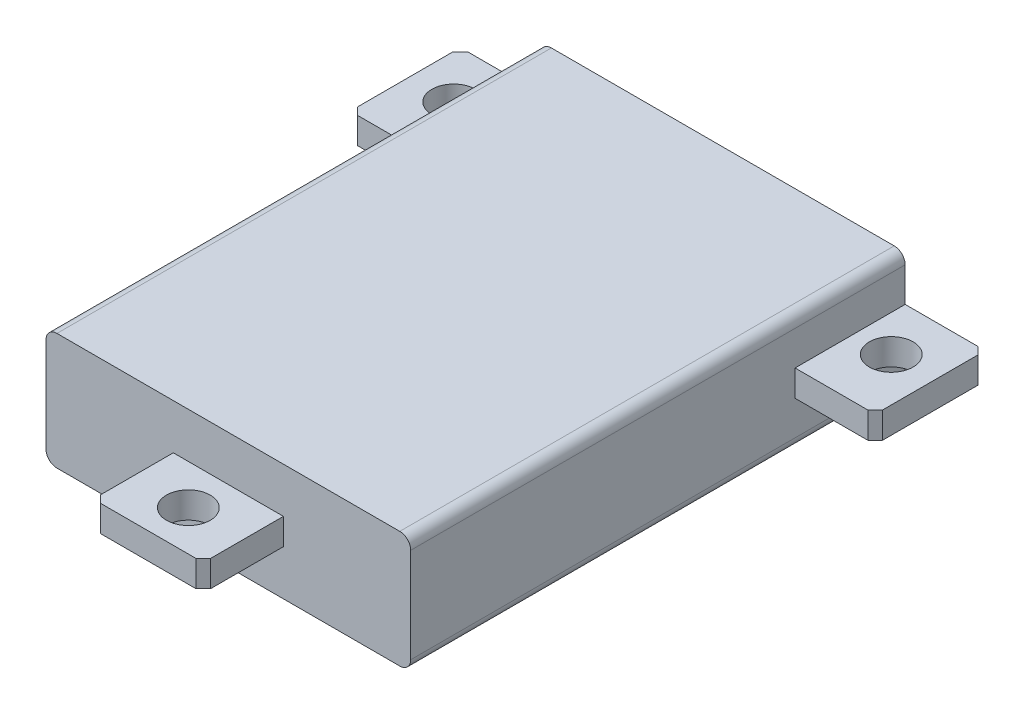
SolidWorks part; units mm, degrees
ref_plane "Front Plane" through (0, 0, 0) normal (0, 0, 1) x (1, 0, 0)
ref_plane "Top Plane" through (0, 0, 0) normal (0, 1, 0) x (1, 0, 0)
ref_plane "Right Plane" through (0, 0, 0) normal (1, 0, 0) x (0, 0, -1)
sketch "Sketch1" plane through (0, 0, 0) normal (0, 1, 0) x (1, 0, 0)
  line L1 (-12.505, -16.9525) -> (12.505, -16.9525)
  line L2 (-12.505, -16.9525) -> (-12.505, 16.9525)
  line L3 (-12.505, 16.9525) -> (12.505, 16.9525)
  line L4 (12.505, -16.9525) -> (12.505, 16.9525)
  line L5 (-12.505, -16.9525) -> (12.505, 16.9525) construction
  line L6 (-12.505, 16.9525) -> (12.505, -16.9525) construction
  point P0 (0, 0)
  dimension "D1" = 33.905
  dimension "D2" = 25.01
extrude "Boss-Extrude1" add sketch "Sketch1" along normal blind 8
sketch "Sketch2" plane through (0, 0, 16.9525) normal (0, 0, 1) x (1, 0, 0)
  line L0 (0, 0) -> (0, 4) construction
  line L2 (-3.775, 3.1) -> (3.775, 3.1)
  line L3 (-3.775, 3.1) -> (-3.775, 4.9)
  line L4 (-3.775, 4.9) -> (3.775, 4.9)
  line L5 (3.775, 3.1) -> (3.775, 4.9)
  line L6 (-3.775, 3.1) -> (3.775, 4.9) construction
  line L7 (-3.775, 4.9) -> (3.775, 3.1) construction
  dimension "D1" = 4
  dimension "D2" = 7.55
  dimension "D3" = 1.8
extrude "Boss-Extrude2" add sketch "Sketch2" along normal blind 5.495
sketch "Sketch3" plane through (-12.505, 0, 0) normal (-1, 0, 0) x (0, 0, 1)
  line L0 (-16.9525, 4) -> (-16.9525, 3.1) construction
  line L1 (-16.9525, 4) -> (-9.4025, 4) construction
  line L3 (-16.9525, 8) -> (-16.9525, 0) construction
  line L4 (-9.4025, 4) -> (-9.4025, 4.9) construction
  line L6 (-16.9525, 3.1) -> (-9.4025, 3.1)
  line L7 (-16.9525, 3.1) -> (-16.9525, 4.9)
  line L8 (-16.9525, 4.9) -> (-9.4025, 4.9)
  line L9 (-9.4025, 3.1) -> (-9.4025, 4.9)
  dimension "D1" = 7.55
  dimension "D2" = 0.9
  dimension "D3" = 0.9
sketch "Sketch4" plane through (-12.505, 0, 0) normal (-1, 0, 0) x (0, 0, 1)
extrude "Boss-Extrude3" add sketch "Sketch3" along normal blind 5.495
mirror "Mirror2" about plane through (0, 0, 0) normal (1, 0, 0) of "Boss-Extrude3"
sketch "Sketch6" plane through (0, 4.9, 0) normal (0, 1, 0) x (1, 0, 0)
  line L0 (3.775, -22.4475) -> (-3.775, -22.4475) construction
  line L1 (15, 13.5025) -> (15, 12.0025) construction
  line L2 (0, -19.6975) -> (1.5, -19.6975) construction
  line L3 (0, -22.4475) -> (0, -19.6975) construction
  line L4 (0, -19.6975) -> (0, 13.5025) construction
  line L5 (-15, 13.5025) -> (15, 13.5025) construction
  line L6 (-15, 13.5025) -> (-15, 12.0025) construction
  circle A0 centre (-15, 13.5025) radius 1.5
  circle A1 centre (15, 13.5025) radius 1.5
  circle A2 centre (0, -19.6975) radius 1.5
  point P0 (0, -22.4475)
  point P6 (0, 13.5025)
  dimension "D4" = 1.5
  dimension "D1" = 2.75
  dimension "D2" = 33.2
  dimension "D3" = 30
  dimension "D5" = 1.5
  dimension "D6" = 1.5
extrude "Cut-Extrude1" cut sketch "Sketch6" against normal blind 2
sketch "Sketch8" plane through (0, 0, -16.9525) normal (0, 0, -1) x (-1, 0, 0)
  line L0 (-12.505, 4.9) -> (-12.505, 3.1) construction
  line L1 (-12.505, 4) -> (-6.555, 4) construction
  circle A0 centre (-6.555, 4) radius 1.5
  dimension "D1" = 5.95
extrude "Cut-Extrude2" cut sketch "Sketch8" against normal blind 3
fillet "Fillet1" radius 0.75 4 edges at (12.505, 0, 0) (12.505, 8, 0) (-12.505, 0, 0) (-12.505, 8, 0)
chamfer "Chamfer1" distance 0.5 angle 45 6 edges at (-18, 4, -16.9525) (-18, 4, -9.4025) (-3.775, 4, 22.4475) (3.775, 4, 22.4475) (18, 4, -9.4025) (18, 4, -16.9525)
equation "\"radius\"= 1.5mm"
